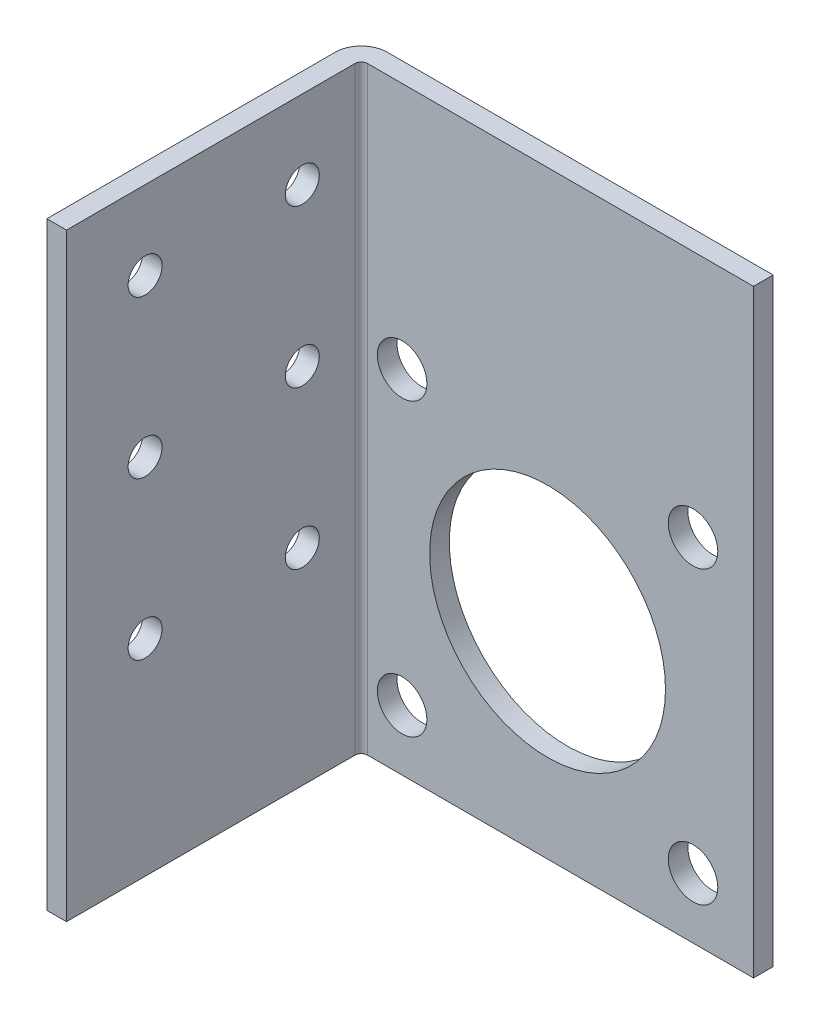
SolidWorks part; units mm, degrees
ref_plane "Front Plane" through (0, 0, 0) normal (0, 0, 1) x (1, 0, 0)
ref_plane "Top Plane" through (0, 0, 0) normal (0, 1, 0) x (1, 0, 0)
ref_plane "Right Plane" through (0, 0, 0) normal (1, 0, 0) x (0, 0, -1)
sketch "Sketch1" plane through (0, 0, 0) normal (0, 0, 1) x (1, 0, 0)
  line L0 (-33.274, -33.274) -> (-33.274, 63.5)
  line L1 (-58.674, 63.5) -> (-33.274, 63.5) construction
  line L2 (-58.674, 63.5) -> (-58.674, -12.7) construction
  line L3 (-58.674, -12.7) -> (-33.274, -12.7) construction
  line L4 (-33.274, 63.5) -> (-33.274, -12.7) construction
  line L5 (-58.674, 63.5) -> (-33.274, -12.7) construction
  line L6 (-58.674, -12.7) -> (-33.274, 63.5) construction
  line L7 (-23.5, -23.5) -> (23.5, -23.5) construction
  line L8 (-23.5, -23.5) -> (-23.5, 23.5) construction
  line L9 (-23.5, 23.5) -> (23.5, 23.5) construction
  line L10 (23.5, -23.5) -> (23.5, 23.5) construction
  line L11 (-23.5, -23.5) -> (23.5, 23.5) construction
  line L12 (-23.5, 23.5) -> (23.5, -23.5) construction
  line L13 (33.274, -33.274) -> (-33.274, -33.274)
  line L14 (33.274, -33.274) -> (33.274, 33.274) construction
  line L15 (33.274, 33.274) -> (-33.274, 33.274) construction
  line L16 (-33.274, -33.274) -> (-33.274, 33.274) construction
  line L17 (33.274, -33.274) -> (-33.274, 33.274) construction
  line L18 (33.274, 33.274) -> (-33.274, -33.274) construction
  line L19 (-33.274, 63.5) -> (33.274, 63.5)
  line L20 (33.274, 63.5) -> (33.274, -33.274)
  circle A0 centre (0, 0) radius 19.05
  circle A1 centre (23.5, 23.5) radius 4
  circle A2 centre (23.5, -23.5) radius 4
  circle A3 centre (-23.5, -23.5) radius 4
  circle A4 centre (-23.5, 23.5) radius 4
  point P7 (-45.974, 25.4)
  dimension "D1" = 38.1
  dimension "D7" = 8
  dimension "D2" = 25.4
  dimension "D3" = 76.2
  dimension "D4" = 33.274
  dimension "D5" = 63.5
  dimension "D6" = 47
extrude "Boss-Extrude3" add sketch "Sketch1" along normal blind 3.175
sketch "Sketch3" plane through (-33.274, 0, 0) normal (-1, 0, 0) x (0, 0, 1)
  line L0 (3.175, -33.274) -> (0, -33.274) construction
  line L1 (0, 63.5) -> (50.8, 63.5)
  line L2 (0, 63.5) -> (0, -33.274)
  line L3 (0, -33.274) -> (50.8, -33.274)
  line L4 (50.8, 63.5) -> (50.8, -33.274)
  line L5 (0, 63.5) -> (50.8, -33.274) construction
  line L6 (0, -33.274) -> (50.8, 63.5) construction
  line L7 (50.8, 0) -> (3.175, 0) construction
  line L8 (3.175, 63.5) -> (3.175, -33.274) construction
  line L9 (50.8, 50.8) -> (3.175, 50.8) construction
  line L10 (50.8, 25.4) -> (3.175, 25.4) construction
  line L11 (38.1, 63.5) -> (38.1, 0) construction
  line L12 (12.7, 63.5) -> (12.7, 0) construction
  circle A0 centre (38.1, 50.8) radius 2.7432
  circle A1 centre (12.7, 50.8) radius 2.7432
  circle A2 centre (38.1, 25.4) radius 2.7432
  circle A3 centre (12.7, 25.4) radius 2.7432
  circle A4 centre (38.1, 0) radius 2.7432
  circle A5 centre (12.7, 0) radius 2.7432
  point P4 (25.4, 15.113)
  point P8 (1.5875, -33.274)
  dimension "D7" = 5.4864
  dimension "D1" = 50.8
  dimension "D2" = 63.5
  dimension "D3" = 38.1
  dimension "D4" = 12.7
  dimension "D5" = 12.7
  dimension "D6" = 38.1
extrude "Boss-Extrude4" add sketch "Sketch3" against normal blind 3.175
fillet "Fillet2" radius 1.016 1 edges at (-30.099, 15.113, 3.175)
fillet "Fillet3" radius 4.191 1 edges at (-33.274, 15.113, 0)
